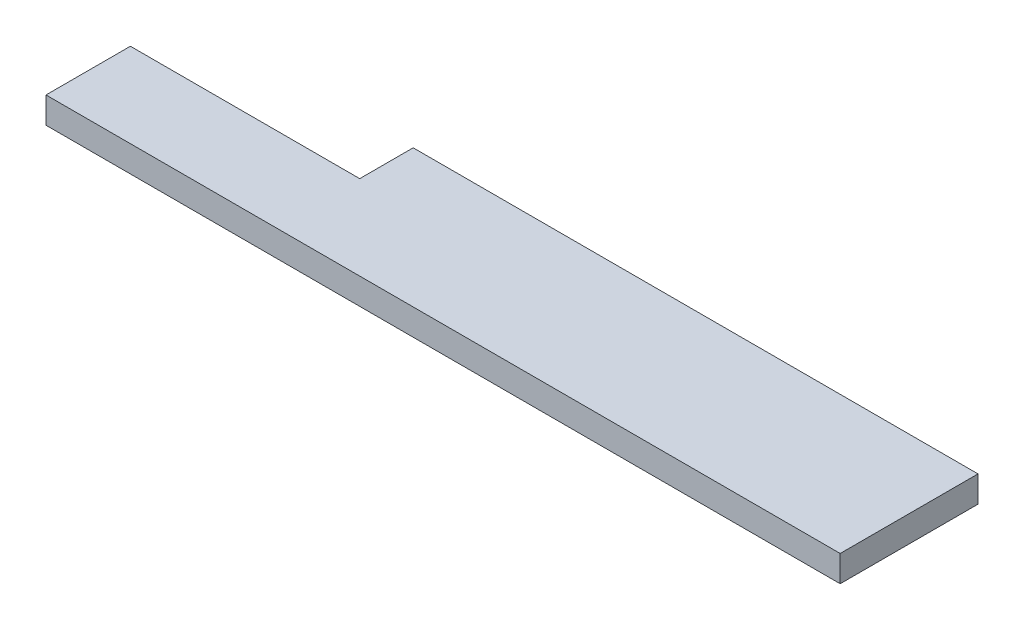
SolidWorks part; units mm, degrees
ref_plane "Front Plane" through (0, 0, 0) normal (0, 0, 1) x (1, 0, 0)
ref_plane "Top Plane" through (0, 0, 0) normal (0, 1, 0) x (1, 0, 0)
ref_plane "Right Plane" through (0, 0, 0) normal (1, 0, 0) x (0, 0, -1)
sketch "Sketch1" plane through (0, 0, 0) normal (0, 1, 0) x (1, 0, 0)
  line L1 (-60.5, -10.5) -> (60.5, -10.5)
  line L2 (-60.5, -10.5) -> (-60.5, 10.5)
  line L3 (-60.5, 10.5) -> (60.5, 10.5)
  line L4 (60.5, -10.5) -> (60.5, 10.5)
  line L5 (-60.5, -10.5) -> (60.5, 10.5) construction
  line L6 (-60.5, 10.5) -> (60.5, -10.5) construction
  point P0 (0, 0)
  dimension "D1" = 121
  dimension "D2" = 21
extrude "Boss-Extrude1" add sketch "Sketch1" along normal blind 4
sketch "Sketch2" plane through (0, 0, 0) normal (0, 1, 0) x (1, 0, 0)
  line L0 (60.5, 10.5) -> (-60.5, 10.5) construction
  line L1 (-62.1511, 10.5) -> (-25.5575, 10.5)
  line L2 (-62.1511, 10.5) -> (-62.1511, 2.3572)
  line L3 (-62.1511, 2.3572) -> (-25.5575, 2.3572)
  line L4 (-25.5575, 10.5) -> (-25.5575, 2.3572)
extrude "Cut-Extrude1" cut sketch "Sketch2" along normal through all both
